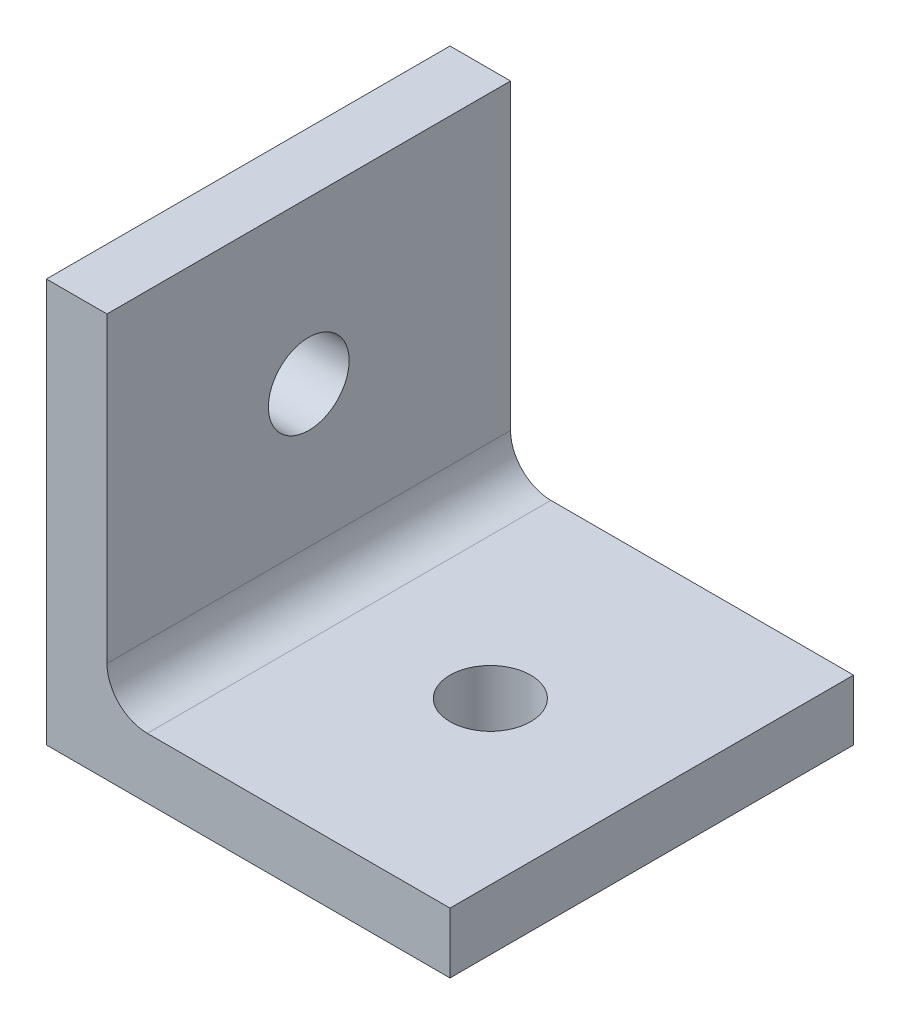
SolidWorks part; units mm, degrees
ref_plane "Płaszczyzna przednia" through (0, 0, 0) normal (0, 0, 1) x (1, 0, 0)
ref_plane "Płaszczyzna górna" through (0, 0, 0) normal (0, 1, 0) x (1, 0, 0)
ref_plane "Płaszczyzna prawa" through (0, 0, 0) normal (1, 0, 0) x (0, 0, -1)
sketch "Sketch1" plane through (0, 0, 0) normal (0, 0, 1) x (1, 0, 0)
  line L0 (3, 3) -> (20, 3)
  line L1 (0, 0) -> (3, 0)
  line L2 (0, 0) -> (0, 20)
  line L3 (0, 20) -> (3, 20)
  line L5 (0, 0) -> (3, 20) construction
  line L6 (0, 20) -> (3, 0) construction
  line L7 (0, 0) -> (20, 0)
  line L8 (0, 0) -> (0, 3)
  line L10 (20, 0) -> (20, 3)
  line L11 (0, 0) -> (20, 3) construction
  line L12 (0, 3) -> (20, 0) construction
  line L13 (3, 3) -> (3, 20)
  point P4 (1.5, 10)
  point P9 (10, 1.5)
  dimension "D1" = 20
  dimension "D2" = 20
  dimension "D3" = 3
  dimension "D4" = 3
extrude "Boss-Extrude1" add sketch "Sketch1" along normal blind 20 contours L0 L13 L3 L2 L1 L7 L10
fillet "Fillet1" radius 2 1 edges at (3, 3, 10)
hole_wizard "Ø4.0mm Dowel Hole1" positions "Sketch2" profile "Sketch3" hole size "Ø4.0" standard "ANSI Metric" end condition through all
sketch "Sketch2" plane through (3, 0, 0) normal (1, 0, 0) x (0, 0, -1)
  line L0 (-20, 5) -> (-20, 20) construction
  line L2 (-20, 20) -> (0, 20) construction
  point P0 (-10, 12)
  dimension "D1" = 10
  dimension "D2" = 8
sketch "Sketch3" plane through (3, 12, 10) normal (0, 1, 0) x (0, 0, -1)
  line L0 (0, 0) -> (0, 3)
  line L1 (0, 3) -> (2, 3)
  line L2 (2, 3) -> (2, 0)
  line L5 (2, 0) -> (0, 0)
  line L11 (0, -6.35) -> (0, 107.95) construction
  dimension "Thru Hole Dia." = 4
  dimension "Thru Hole Depth" = 3
hole_wizard "Ø4.0mm Dowel Hole2" positions "Sketch4" profile "Sketch5" hole size "Ø4.0" standard "ANSI Metric" end condition through all
sketch "Sketch4" plane through (0, 3, 0) normal (0, 1, 0) x (1, 0, 0)
  line L0 (5, -20) -> (20, -20) construction
  line L2 (20, -20) -> (20, 0) construction
  point P0 (12, -10)
  dimension "D1" = 10
  dimension "D2" = 8
sketch "Sketch5" plane through (12, 3, 10) normal (1, 0, 0) x (0, 0, 1)
  line L0 (0, 0) -> (0, 3)
  line L1 (0, 3) -> (2, 3)
  line L2 (2, 3) -> (2, 0)
  line L5 (2, 0) -> (0, 0)
  line L11 (0, -6.35) -> (0, 107.95) construction
  dimension "Thru Hole Dia." = 4
  dimension "Thru Hole Depth" = 3
